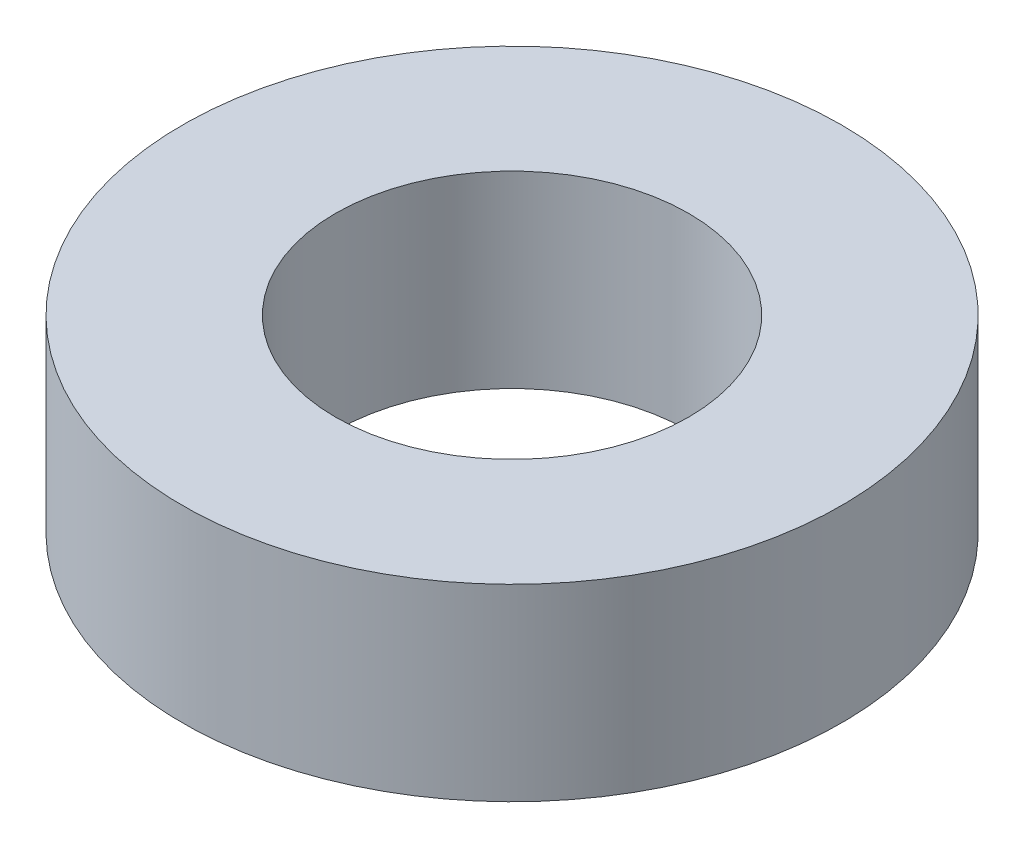
SolidWorks part; units mm, degrees
material "6061"
ref_plane "Front" through (0, 0, 0) normal (0, 0, 1) x (1, 0, 0)
ref_plane "Top" through (0, 0, 0) normal (0, 1, 0) x (1, 0, 0)
ref_plane "Right" through (0, 0, 0) normal (1, 0, 0) x (0, 0, -1)
sketch "Sketch1" plane through (0, 0, 0) normal (0, 0, 1) x (1, 0, 0)
  line L0 (0, -5.6814) -> (0, 44.5674) construction
  line L2 (7.5, 0) -> (14, 0)
  line L3 (7.5, 0) -> (7.5, 8)
  line L4 (7.5, 8) -> (14, 8)
  line L5 (14, 0) -> (14, 8)
  dimension "D1" = 28
  dimension "D2" = 15
  dimension "D3" = 8
revolve "Revolve1" add sketch "Sketch1" angle 360 about L0
